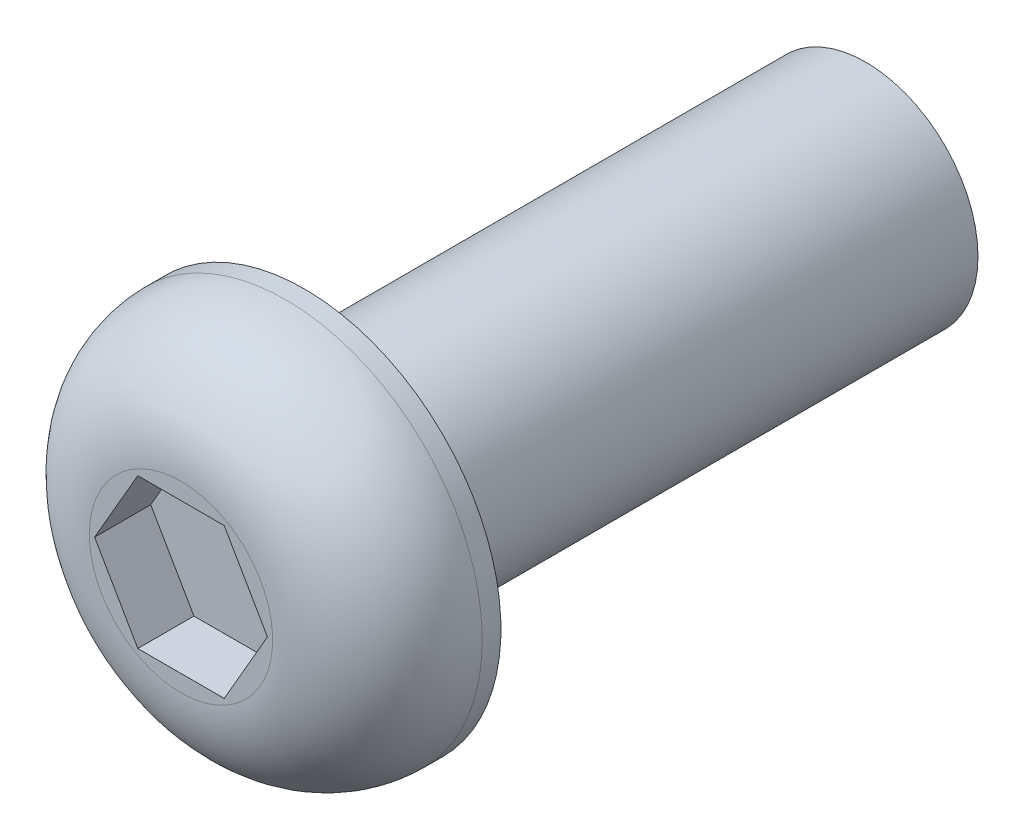
SolidWorks part; units mm, degrees
material "AISI 304"
ref_plane "Front Plane" through (0, 0, 0) normal (0, 0, 1) x (1, 0, 0)
ref_plane "Top Plane" through (0, 0, 0) normal (0, 1, 0) x (1, 0, 0)
ref_plane "Right Plane" through (0, 0, 0) normal (1, 0, 0) x (0, 0, -1)
sketch "Sketch1" plane through (0, 0, 0) normal (0, 0, 1) x (1, 0, 0)
  circle A0 centre (0, 0) radius 6
  dimension "D1" = 12
extrude "Extrude1" add sketch "Sketch1" against normal blind 30
sketch "Sketch2" plane through (0, 0, 0) normal (1, 0, 0) x (0, 0, -1)
  line L0 (0, 0) -> (-10.9859, 0) construction
  line L1 (0, 0) -> (0, 10.5)
  line L2 (0, 10.5) -> (-1, 10.5)
  line L3 (-6.6, 0) -> (-6.6, 4.9)
  line L4 (0, 0) -> (-6.6, 0)
  arc A0 (-6.6, 4.9) -> (-1, 10.5) centre (-1, 4.9) cw
  dimension "D1" = 6.6
  dimension "D2" = 21
  dimension "D3" = 1
revolve "Revolve1" add sketch "Sketch2" angle 360 about L0
sketch "Sketch3" plane through (0, 0, 6.6) normal (0, 0, 1) x (1, 0, 0)
  line L1 (-2.3094, 4) -> (-4.6188, 0)
  line L2 (-4.6188, 0) -> (-2.3094, -4)
  line L3 (-2.3094, -4) -> (2.3094, -4)
  line L4 (2.3094, -4) -> (4.6188, 0)
  line L5 (4.6188, 0) -> (2.3094, 4)
  line L6 (2.3094, 4) -> (-2.3094, 4)
  circle A0 centre (0, 0) radius 4 construction
  dimension "D1" = 8
extrude "Cut-Extrude1" cut sketch "Sketch3" against normal blind 3
